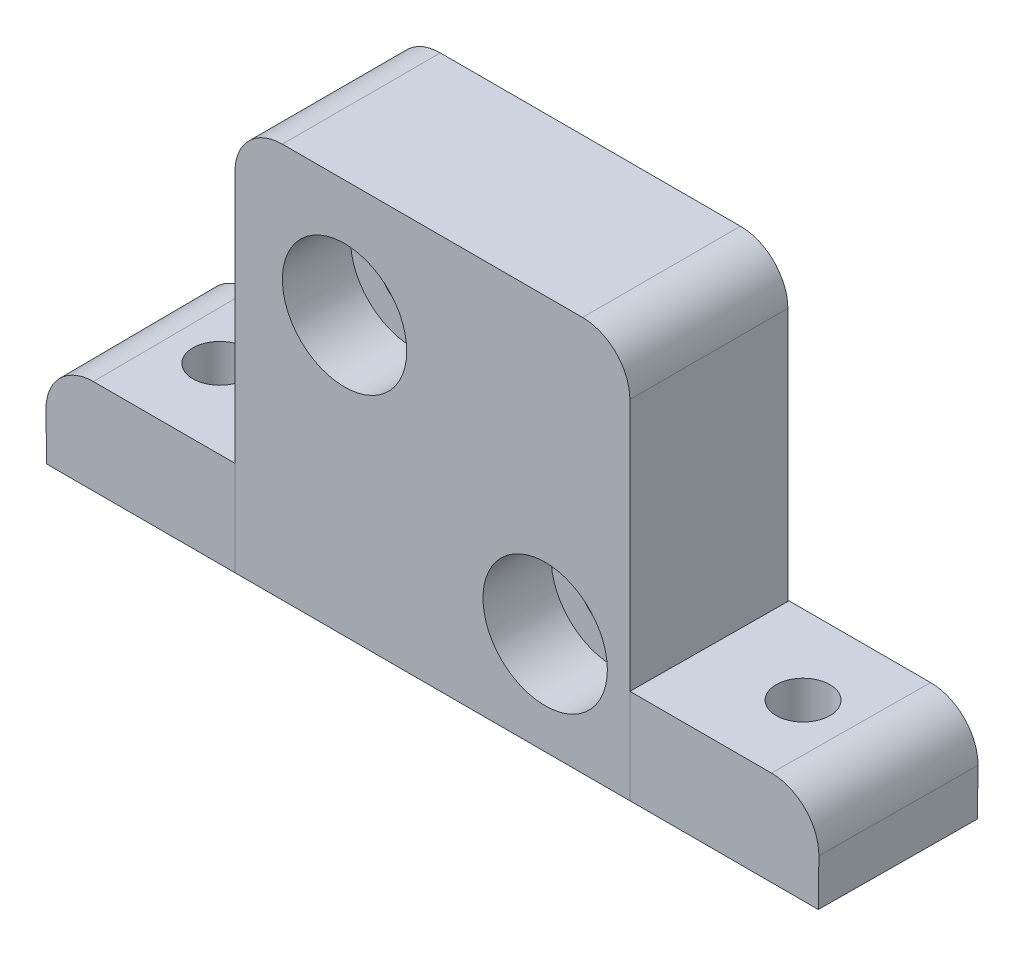
SolidWorks part; units mm, degrees
ref_plane "Front Plane" through (0, 0, 0) normal (0, 0, 1) x (1, 0, 0)
ref_plane "Top Plane" through (0, 0, 0) normal (0, 1, 0) x (1, 0, 0)
ref_plane "Right Plane" through (0, 0, 0) normal (1, 0, 0) x (0, 0, -1)
sketch "Sketch1" plane through (0, 0, 0) normal (0, 0, 1) x (1, 0, 0)
  line L1 (-12.5, -12.5) -> (12.5, -12.5)
  line L2 (-12.5, -12.5) -> (-12.5, 12.5)
  line L3 (-12.5, 12.5) -> (12.5, 12.5)
  line L4 (12.5, -12.5) -> (12.5, 12.5)
  line L5 (-12.5, -12.5) -> (12.5, 12.5) construction
  line L6 (-12.5, 12.5) -> (12.5, -12.5) construction
  circle A0 centre (-5.563, 5.0876) radius 2.2225
  circle A1 centre (7.137, -6.0376) radius 2.2225
  point P0 (0, 0)
  dimension "D7" = 4.445
  dimension "D8" = 4.445
  dimension "D1" = 25
  dimension "D2" = 25
  dimension "D3" = 6.937
  dimension "D4" = 12.7
  dimension "D5" = 6.4624
  dimension "D6" = 11.1252
extrude "Boss-Extrude1" add sketch "Sketch1" along normal blind 10
sketch "Sketch2" plane through (0, 0, 10) normal (0, 0, 1) x (1, 0, 0)
  circle A0 centre (-5.563, 5.0876) radius 3.937
  circle A1 centre (7.137, -6.0376) radius 3.937
  dimension "D1" = 7.874
  dimension "D2" = 7.874
extrude "Cut-Extrude3" cut sketch "Sketch2" against normal blind 4.318
sketch3d "3DSketch1"
  line L5 (-12.5, 12.5, 10) -> (-12.5, -12.5, 10) construction
  line L6 (-12.5, -12.5, 0) -> (-12.5738, -6.5005, 0.0003)
  line L7 (-12.5, -12.5, 0) -> (-12.4262, -12.4995, 9.9997)
  line L8 (-12.4262, -12.4995, 9.9997) -> (-12.5, -6.5, 10)
  line L9 (-12.5738, -6.5005, 0.0003) -> (-12.5, -6.5, 10)
  dimension "D3" = 10
  dimension "D4" = 6
extrude "Boss-Extrude2" add sketch "3DSketch1" along direction (1, 0, 0) on the side of the normal blind 12
mirror "Mirror1" about plane through (0, 0, 0) normal (1, 0, 0) of "Boss-Extrude2"
fillet "Fillet1" radius 3 2 edges at (12.5, 12.5, 5) (-12.5, 12.5, 5)
sketch "Sketch3" plane through (0, -12.5, 0) normal (0, -1, 0) x (1, 0, 0)
  line L0 (-24.4631, 4.9999) -> (24.4631, 4.9999) construction
  line L1 (-24.5, 0) -> (-24.4262, 9.9997) construction
  line L2 (24.5, 0) -> (24.4262, 9.9997) construction
  circle A0 centre (-18.4629, 4.9999) radius 1.7
  circle A1 centre (18.4629, 4.9999) radius 1.7
  dimension "D1" = 3.4
  dimension "D2" = 3.4
  dimension "D3" = 6
  dimension "D4" = 6
extrude "Cut-Extrude4" cut sketch "Sketch3" against normal up to surface (5.9997 mm away) up to face at (-15.5184, -6.5001, 7.5001)
fillet "Fillet2" radius 3 2 edges
